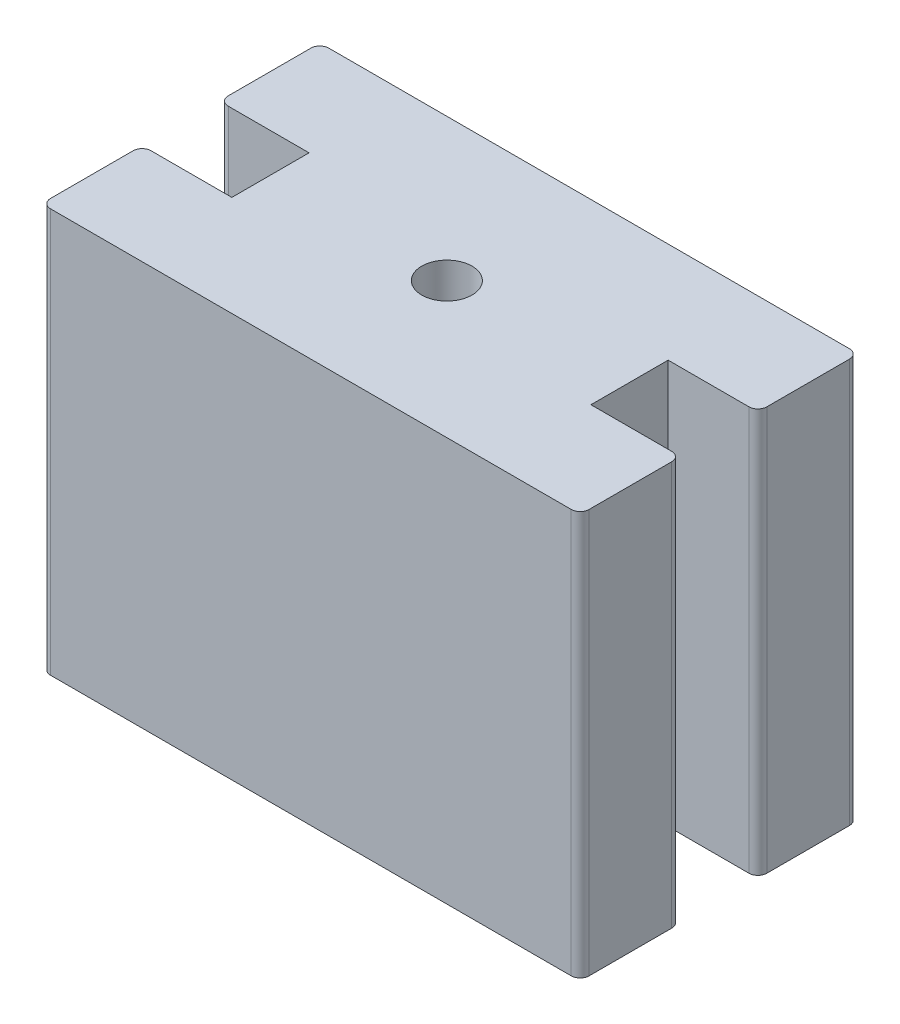
SolidWorks part; units mm, degrees
ref_plane "Front Plane" through (0, 0, 0) normal (0, 0, 1) x (1, 0, 0)
ref_plane "Top Plane" through (0, 0, 0) normal (0, 1, 0) x (1, 0, 0)
ref_plane "Right Plane" through (0, 0, 0) normal (1, 0, 0) x (0, 0, -1)
sketch "Sketch1" plane through (0, 0, 0) normal (0, 1, 0) x (1, 0, 0)
  line L0 (20, 4.65) -> (29, 4.65)
  line L1 (-20, 15.85) -> (20, 15.85)
  line L2 (-20, 4.65) -> (-20, -3.95)
  line L3 (-20, -15.15) -> (20, -15.15)
  line L4 (20, 4.65) -> (20, -3.95)
  line L7 (-29, 15.85) -> (29, 15.85)
  line L8 (-30, 14.85) -> (-30, 5.65)
  line L9 (-29, 4.65) -> (-20, 4.65)
  line L10 (30, 14.85) -> (30, 5.65)
  line L11 (-29, -15.15) -> (29, -15.15)
  line L12 (-30, -14.15) -> (-30, -4.95)
  line L13 (-29, -3.95) -> (-20, -3.95)
  line L14 (30, -14.15) -> (30, -4.95)
  line L15 (20, -3.95) -> (29, -3.95)
  arc A0 (-29, -15.15) -> (-30, -14.15) centre (-29, -14.15) cw
  arc A1 (-30, -4.95) -> (-29, -3.95) centre (-29, -4.95) cw
  arc A2 (-30, 5.65) -> (-29, 4.65) centre (-29, 5.65) ccw
  arc A3 (-29, 15.85) -> (-30, 14.85) centre (-29, 14.85) ccw
  arc A4 (29, -15.15) -> (30, -14.15) centre (29, -14.15) ccw
  arc A5 (29, -3.95) -> (30, -4.95) centre (29, -4.95) cw
  arc A6 (29, 4.65) -> (30, 5.65) centre (29, 5.65) ccw
  arc A7 (29, 15.85) -> (30, 14.85) centre (29, 14.85) cw
  circle A8 centre (0, 0) radius 2.8
  point P0 (0, 0)
  dimension "D6" = 1
  dimension "D7" = 1
  dimension "D8" = 5.6
  dimension "D1" = 40
  dimension "D2" = 31
  dimension "D3" = 8.6
  dimension "D4" = 10
  dimension "D5" = 10
extrude "Boss-Extrude1" add sketch "Sketch1" along normal blind 45 contours A7 L7 L1 A3 L8 A2 L9 L2 L13 A1 L12 A0 L11 L3 A4 L14 A5 L15 L4 L0 A6 L10 A8
